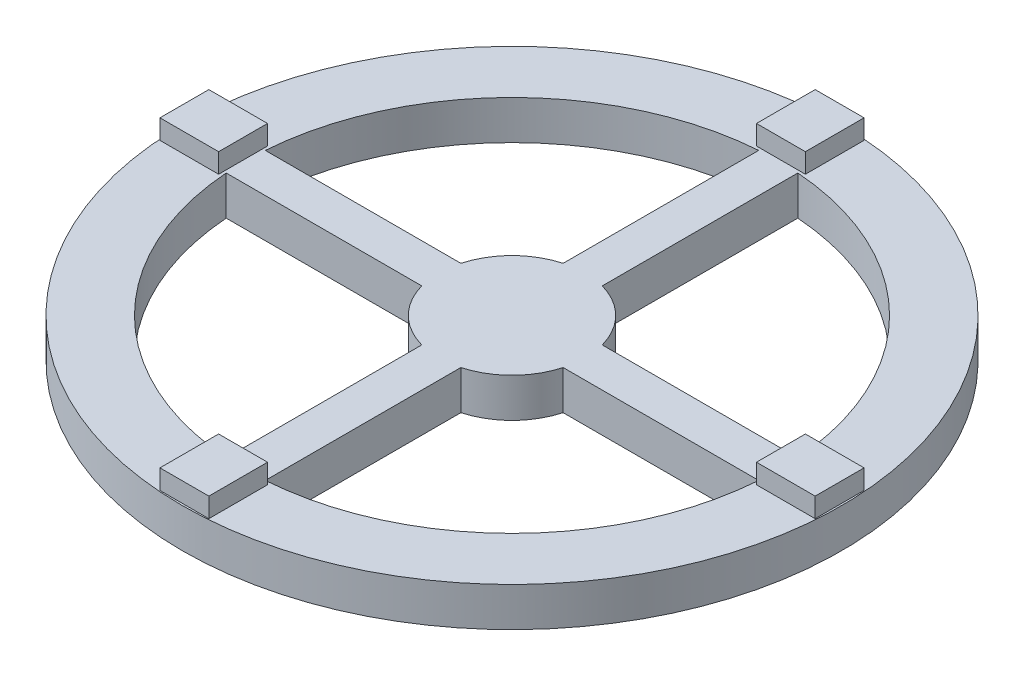
SolidWorks part; units mm, degrees
ref_plane "Front Plane" through (0, 0, 0) normal (0, 0, 1) x (1, 0, 0)
ref_plane "Top Plane" through (0, 0, 0) normal (0, 1, 0) x (1, 0, 0)
ref_plane "Right Plane" through (0, 0, 0) normal (1, 0, 0) x (0, 0, -1)
sketch "Sketch2" plane through (0, 0, 0) normal (0, 0, 1) x (1, 0, 0)
  line L0 (0, 0) -> (300, 0) construction
  line L1 (0, 0) -> (0, 32.0062) construction
  circle A0 centre (300, 0) radius 20
  dimension "D2" = 40
  dimension "D1" = 300
revolve "Revolve1" add sketch "Sketch2" angle 360 about L1
ref_plane "Plane2" through (0, 0, 300) normal (0, 0, 1) x (1, 0, 0)
sketch "Sketch3" plane through (0, 0, 300) normal (0, 0, 1) x (1, 0, 0)
  line L0 (-11.2372, 20) -> (12.3437, 20) construction
  line L1 (300, 20) -> (-300, 20) construction
  line L3 (-20, -20) -> (20, -20)
  line L4 (-20, -20) -> (-20, 20)
  line L5 (-20, 20) -> (20, 20)
  line L6 (20, -20) -> (20, 20)
  line L7 (-20, -20) -> (20, 20) construction
  line L8 (-20, 20) -> (20, -20) construction
  circle A0 centre (0, 0) radius 20 construction
  point P3 (0, 20)
extrude "Boss-Extrude1" add sketch "Sketch3" against normal blind 225
sketch "Sketch4" plane through (0, 0, 0) normal (0, 0, 1) x (1, 0, 0)
  line L0 (0, 97.1114) -> (0, -106.1101) construction
pattern_circular "CirPattern1" count 4 over 360 about axis through (0, 0, 0) along (0, 1, 0) of "Boss-Extrude1"
sketch "Sketch5" plane through (0, 0, 0) normal (0, 1, 0) x (1, 0, 0)
  point P22 (0, 0)
sketch "Sketch6" plane through (0, 0, 0) normal (0, 1, 0) x (1, 0, 0)
  line L0 (0, -300) -> (0, 0) construction
  circle A0 centre (0, 0) radius 300 construction
  dimension "D1" = 600
sketch "Sketch8" plane through (0, 0, 0) normal (0, 1, 0) x (1, 0, 0)
  line L0 (273, 0) -> (305, 0) construction
  line L1 (305, 0) -> (337, 0) construction
  circle A0 centre (0, 0) radius 337
  circle A1 centre (0, 0) radius 273
  circle A2 centre (0, 0) radius 305 construction
  dimension "D1" = 32
  dimension "D3" = 610
extrude "Boss-Extrude3" add sketch "Sketch8" along normal mid plane 40
sketch "Sketch9" plane through (0, 0, 0) normal (0, 1, 0) x (1, 0, 0)
  line L0 (-20, -75) -> (-20, -72.2842)
  line L1 (20, -75) -> (20, -72.2842)
  line L11 (-75, -20) -> (-72.2842, -20)
  line L12 (-75, 20) -> (-72.2842, 20)
  line L13 (-20, 75) -> (-20, 72.2842)
  line L14 (20, 75) -> (20, 72.2842)
  line L15 (75, 20) -> (72.2842, 20)
  line L16 (75, -20) -> (72.2842, -20)
  line L17 (-20, 75) -> (20, 75)
  line L18 (75, 20) -> (75, -20)
  line L19 (-20, -75) -> (20, -75)
  line L20 (-75, 20) -> (-75, -20)
  arc A1 (-72.2842, -20) -> (-20, -72.2842) centre (0, 0) ccw
  arc A2 (20, -72.2842) -> (72.2842, -20) centre (0, 0) ccw
  arc A3 (72.2842, 20) -> (20, 72.2842) centre (0, 0) ccw
  arc A4 (-20, 72.2842) -> (-72.2842, 20) centre (0, 0) ccw
  point P24 (0, 0)
  dimension "D1" = 150
  dimension "D2" = 4
extrude "Boss-Extrude4" add sketch "Sketch9" along normal mid plane 40
sketch "Sketch10" plane through (0, -20, 0) normal (0, -1, 0) x (1, 0, 0)
  line L0 (0, 300) -> (0, 0) construction
  line L1 (0, 300) -> (0, 0) construction
  circle A0 centre (0, 0) radius 300 construction
  circle A1 centre (0, 0) radius 300 construction
sketch "Sketch11" plane through (0, 20, 0) normal (0, 1, 0) x (1, 0, 0)
  circle A0 centre (0, 0) radius 35 construction
  dimension "D1" = 70
sketch "Sketch12" plane through (0, 20, 0) normal (0, 1, 0) x (1, 0, 0)
  line L0 (0, 273) -> (0, 305) construction
  line L1 (275, -25) -> (335, -25)
  line L2 (275, -25) -> (275, 25)
  line L3 (275, 25) -> (335, 25)
  line L4 (335, -25) -> (335, 25)
  line L5 (275, -25) -> (335, 25) construction
  line L6 (275, 25) -> (335, -25) construction
  line L7 (0, 305) -> (0, 337) construction
  line L8 (305, 0) -> (0, 0) construction
  line L9 (-25, -275) -> (25, -275)
  line L10 (-25, -275) -> (-25, -335)
  line L11 (-25, -335) -> (25, -335)
  line L12 (25, -275) -> (25, -335)
  line L13 (-25, -275) -> (25, -335) construction
  line L14 (25, -275) -> (-25, -335) construction
  line L15 (-275, 25) -> (-275, -25)
  line L16 (-275, 25) -> (-335, 25)
  line L17 (-335, 25) -> (-335, -25)
  line L18 (-275, -25) -> (-335, -25)
  line L19 (-275, 25) -> (-335, -25) construction
  line L20 (-275, -25) -> (-335, 25) construction
  line L21 (25, 275) -> (-25, 275)
  line L22 (25, 275) -> (25, 335)
  line L23 (25, 335) -> (-25, 335)
  line L24 (-25, 275) -> (-25, 335)
  line L25 (25, 275) -> (-25, 335) construction
  line L26 (-25, 275) -> (25, 335) construction
  circle A0 centre (0, 0) radius 305 construction
  circle A3 centre (0, 0) radius 337 construction
  arc A4 (-20, 272.2664) -> (-272.2664, 20) centre (0, 0) ccw construction
  point P0 (305, 0)
  point P19 (0, 305)
  point P33 (0, 0)
  dimension "D3" = 4
  dimension "D1" = 60
  dimension "D2" = 50
extrude "Boss-Extrude5" add sketch "Sketch12" along normal blind 20
